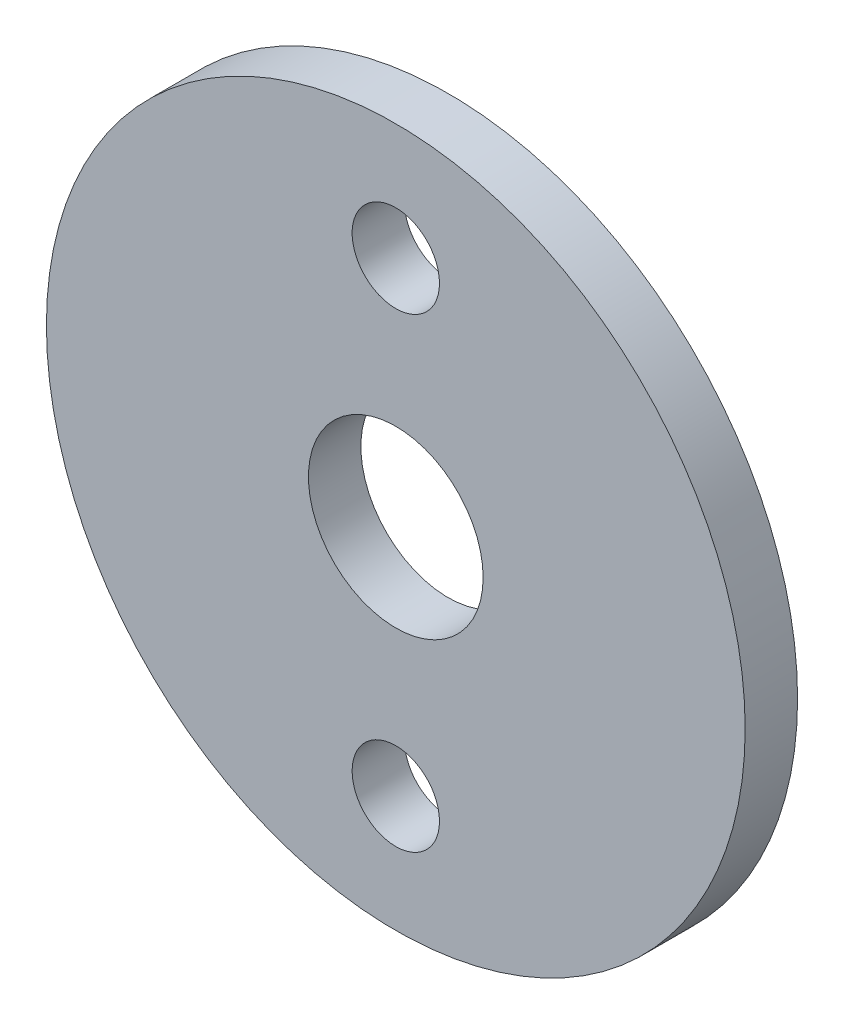
SolidWorks part; units mm, degrees
ref_plane "Plan de face" through (0, 0, 0) normal (0, 0, 1) x (1, 0, 0)
ref_plane "Plan de dessus" through (0, 0, 0) normal (0, 1, 0) x (1, 0, 0)
ref_plane "Plan de droite" through (0, 0, 0) normal (1, 0, 0) x (0, 0, -1)
sketch "Esquisse1" plane through (0, 0, 0) normal (0, 0, 1) x (1, 0, 0)
  circle A0 centre (0, 0) radius 12
  circle A1 centre (0, 0) radius 3
  dimension "D1" = 24
  dimension "D2" = 6
extrude "Boss.-Extru.1" add sketch "Esquisse1" along normal blind 1.8
sketch "Esquisse2" plane through (0, 0, 1.8) normal (0, 0, 1) x (1, 0, 0)
  line L0 (-12, 0) -> (12, 0) construction
  line L1 (0, 12) -> (0, -12) construction
  circle A0 centre (0, 8) radius 1.5
  circle A1 centre (0, 0) radius 12 construction
  circle A2 centre (0, -8) radius 1.5
  dimension "D1" = 3
  dimension "D2" = 4
extrude "Enlèv. mat.-Extru.1" cut sketch "Esquisse2" against normal up to next
